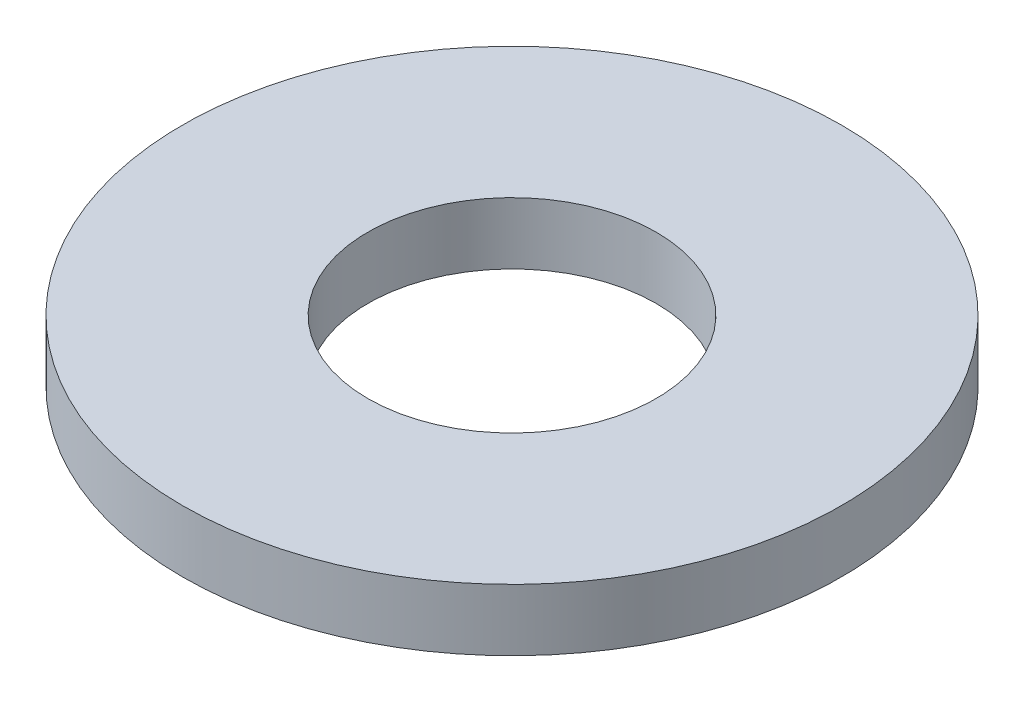
SolidWorks part; units mm, degrees
ref_plane "Front" through (0, 0, 0) normal (0, 0, 1) x (1, 0, 0)
ref_plane "Top" through (0, 0, 0) normal (0, 1, 0) x (1, 0, 0)
ref_plane "Right" through (0, 0, 0) normal (1, 0, 0) x (0, 0, -1)
sketch "Sketch1" plane through (0, 0, 0) normal (0, 1, 0) x (1, 0, 0)
  circle A0 centre (0, 0) radius 8.128
  circle A1 centre (0, 0) radius 3.556
  dimension "D1" = 16.256
  dimension "D2" = 7.112
extrude "Extrude1" add sketch "Sketch1" along normal blind 1.524
